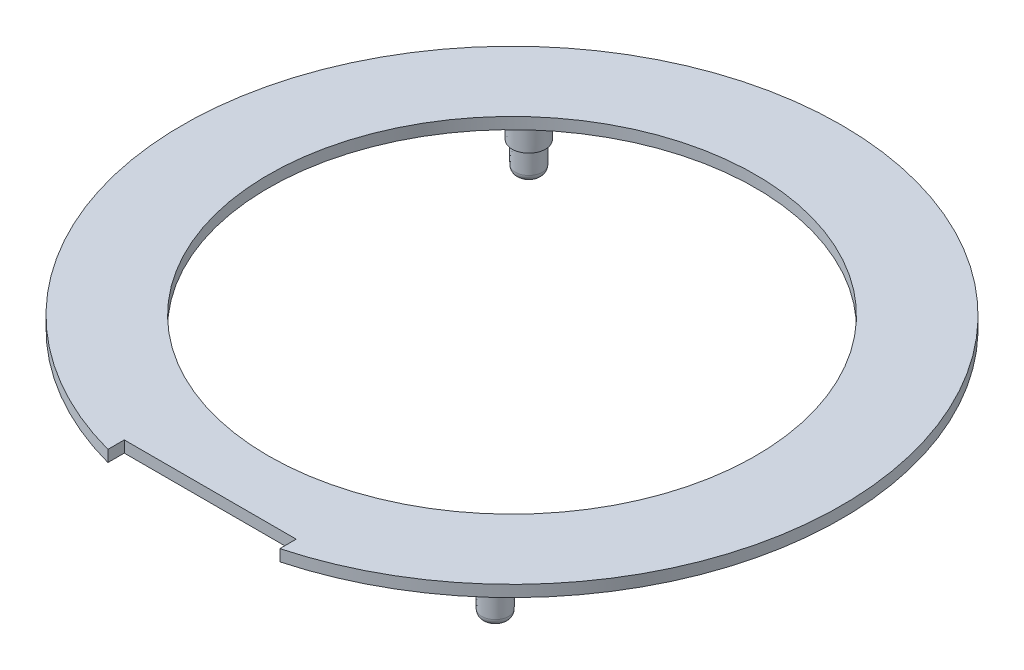
SolidWorks part; units mm, degrees
ref_plane "Front Plane" through (0, 0, 0) normal (0, 0, 1) x (1, 0, 0)
ref_plane "Top Plane" through (0, 0, 0) normal (0, 1, 0) x (1, 0, 0)
ref_plane "Right Plane" through (0, 0, 0) normal (1, 0, 0) x (0, 0, -1)
sketch "Sketch1" plane through (0, 0, 0) normal (0, 1, 0) x (1, 0, 0)
  circle A0 centre (0, 1.5306) radius 11.5
  circle A1 centre (0, 1.5306) radius 8.5
  dimension "D1" = 23
  dimension "D2" = 17
  dimension "D3" = 1.5306
extrude "Boss-Extrude1" add sketch "Sketch1" along normal blind 0.4
sketch "Sketch2" plane through (0, 0, 0) normal (0, 1, 0) x (1, 0, 0)
  line L0 (0, 1.5306) -> (-7.0041, -4.8875) construction
  line L1 (0, 1.5306) -> (0, -4.7232) construction
  circle A0 centre (-7.0041, -4.8875) radius 0.6
  point P13 (0, 0)
  dimension "D2" = 1.2
  dimension "D1" = 9.5
  dimension "D3" = 47.5
extrude "Boss-Extrude2" add sketch "Sketch2" against normal blind 1
sketch "Sketch3" plane through (0, -1, 0) normal (0, -1, 0) x (1, 0, 0)
  circle A0 centre (-7.0041, 4.8875) radius 0.5
  dimension "D1" = 1
extrude "Boss-Extrude3" add sketch "Sketch3" along normal blind 1
pattern_circular "CirPattern1" count 4 over 360 about axis through (0, 0, -1.5306) along (0, 1, 0) of "Boss-Extrude2", "Boss-Extrude3"
sketch "Sketch4" plane through (0, 0.4, 0) normal (0, 1, 0) x (1, 0, 0)
  line L0 (-0.75, 13.0062) -> (-0.75, 11.001) construction
  line L1 (0, -1.32) -> (0, 1.32) construction
  line L2 (0.75, 13.0062) -> (0.75, 11.001) construction
  circle A0 centre (0, 1.5306) radius 9.5 construction
  circle A1 centre (0, 1.5306) radius 11.5 construction
  circle A2 centre (0, 1.5306) radius 11.5 construction
  dimension "D1" = 19
  dimension "D3" = 1.5
sketch "Sketch5" plane through (0, 0.4, 0) normal (0, 1, 0) x (1, 0, 0)
  line L0 (-0.75, 13.0062) -> (-0.75, 11.001) construction
  line L1 (-0.75, 13.0062) -> (-0.75, 11.001)
  line L2 (0.75, 13.0062) -> (0.75, 11.001) construction
  line L3 (0.75, 13.0062) -> (0.75, 11.001)
  circle A0 centre (0, 1.5306) radius 11.5 construction
  arc A1 (0.75, 13.0062) -> (-0.75, 13.0062) centre (0, 1.5306) ccw
  circle A2 centre (0, 1.5306) radius 9.5 construction
  arc A3 (0.75, 11.001) -> (-0.75, 11.001) centre (0, 1.5306) ccw
draft "Draft1" type of draft neutral plane draft angle 1 faces to draft 8 face at (7.0181, -1, 5.4735) face at (5.9181, -2, 5.4735) face at (7.0041, -1, -8.5488) face at (7.0041, -2, -7.4488) face at (-7.0181, -1, -8.5348) face at (-5.9181, -2, -8.5348) face at (-7.0041, -1, 5.4875) face at (-7.0041, -2, 4.3875) neutral plane through (0, 0, -1.5306) neutral plane normal (0, -1, 0) parameters "D1"=1
fillet "Fillet1" radius 0.25 4 edges at (-7.0041, -2, 4.4224) (7.0041, -2, -8.4138) (6.4181, -2, 5.0084) (-6.4181, -2, -8.9999)
sketch "Sketch6" plane through (0, 0.4, 0) normal (0, 1, 0) x (1, 0, 0)
  line L0 (0, 0) -> (0, -9) construction
  line L1 (3, -9) -> (-3, -9)
  line L2 (-3, -9) -> (-3, -9.5712)
  line L3 (3, -9) -> (3, -9.5712)
  circle A0 centre (0, 1.5306) radius 11.5 construction
  arc A1 (-3, -9.5712) -> (3, -9.5712) centre (0, 1.5306) ccw
  point P6 (0, -9)
  dimension "D1" = 9
  dimension "D2" = 6
  dimension "D3" = 90
extrude "Cut-Extrude1" cut sketch "Sketch6" against normal up to surface (0.4 mm away) up to face at (7.0181, 0, 5.4735)
